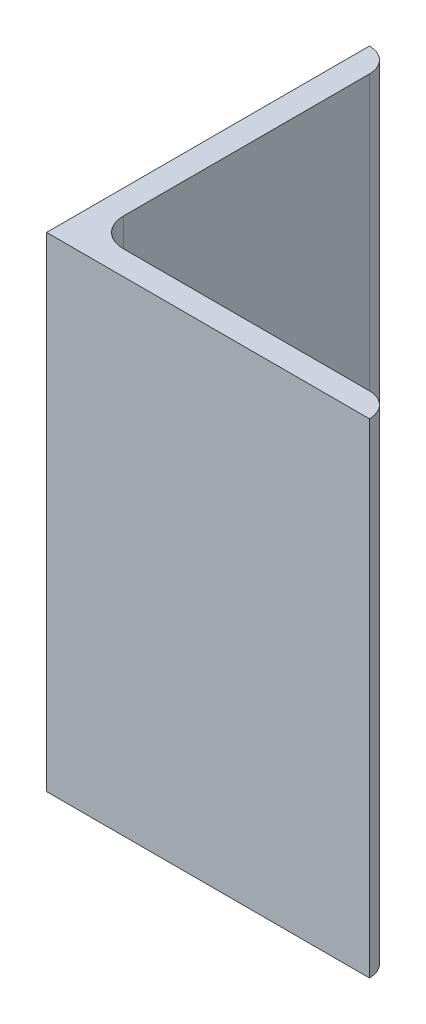
SolidWorks part; units mm, degrees
ref_plane "Front Plane" through (0, 0, 0) normal (0, 0, 1) x (1, 0, 0)
ref_plane "Top Plane" through (0, 0, 0) normal (0, 1, 0) x (1, 0, 0)
ref_plane "Right Plane" through (0, 0, 0) normal (1, 0, 0) x (0, 0, -1)
sketch3d "3DSketch1"
  line L0 (0, 0, 0) -> (0, 60, 0)
  dimension "D1" = 60
other "Iron V40X40X3(1)"
ref_plane "Plane1" through (0, 0, 0) normal (0, 1, 0) x (1, 0, 0)
sketch "Sketch11" plane through (0, 0, 0) normal (0, 1, 0) x (1, 0, 0)
  line L0 (0, 0) -> (0, 40)
  line L1 (0, 20) -> (3, 20) construction
  line L2 (3, 37) -> (3, 6.5)
  line L3 (6.5, 3) -> (37, 3)
  line L4 (20, 3) -> (20, 0) construction
  line L5 (40, 0) -> (0, 0)
  arc A0 (40, 0) -> (37, 3) centre (37, 0) ccw
  arc A1 (0, 40) -> (3, 37) centre (0, 37) cw
  arc A2 (6.5, 3) -> (3, 6.5) centre (6.5, 6.5) cw
  point P10 (20, 0)
  point P14 (0, 20)
  point P15 (3, 20)
  point P16 (20, 3)
  point P17 (3, 40)
  point P18 (40, 3)
  point P21 (0, 0)
  dimension "D2" = 3
  dimension "D3" = 40
  dimension "Radius_1" = 3.5
  dimension "D1" = 3
